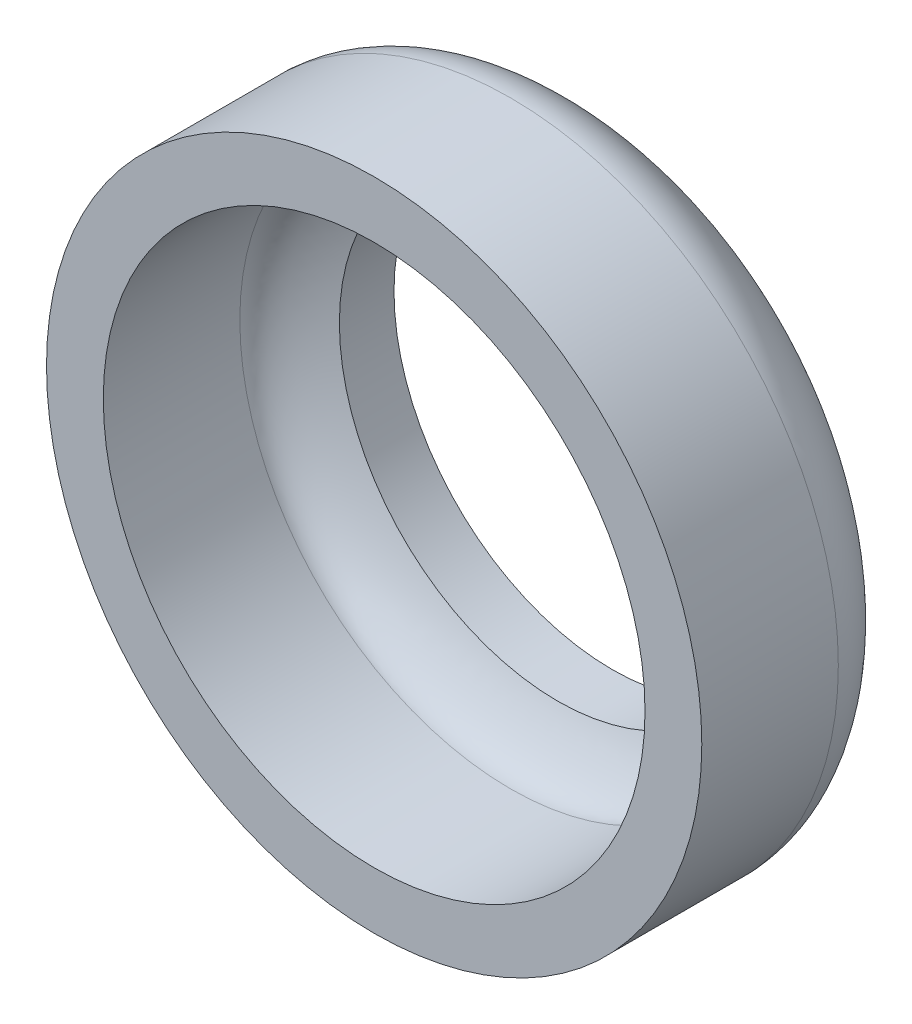
SolidWorks part; units mm, degrees
ref_plane "Front Plane" through (0, 0, 0) normal (0, 0, 1) x (1, 0, 0)
ref_plane "Top Plane" through (0, 0, 0) normal (0, 1, 0) x (1, 0, 0)
ref_plane "Right Plane" through (0, 0, 0) normal (1, 0, 0) x (0, 0, -1)
sketch "Sketch1" plane through (0, 0, 0) normal (1, 0, 0) x (0, 0, -1)
  line L0 (0, -9.525) -> (0, 9.525) construction
  line L1 (0, 0) -> (7.9375, 0) construction
  point P4 (0, 7.874)
  dimension "Tube OD" = 19.05
  dimension "Length" = 7.9375
  dimension "Wall Thickness" = 1.651
sketch "Sketch2" plane through (0, 0, 0) normal (1, 0, 0) x (0, 0, -1)
  line L0 (0, 9.525) -> (3.9688, 9.525)
  line L2 (0, 7.874) -> (3.9688, 7.874)
  line L4 (0, 0) -> (7.9375, 0) construction
  line L5 (6.2865, 0) -> (7.9375, 0)
  line L6 (0, 9.525) -> (0, 7.874)
  ellipse E0 centre (3.9688, 0) end of major axis (3.9688, 9.525) minor radius 3.9688 (7.9375, 0) -> (3.9688, 9.525) ccw
  ellipse E1 centre (3.9688, 0) end of major axis (3.9688, 7.874) minor radius 2.3178 (6.2865, 0) -> (3.9688, 7.874) ccw
revolve "Revolve1" add sketch "Sketch2" angle 360 about L1
sketch "Sketch3" plane through (0, 0, 0) normal (0, 0, 1) x (1, 0, 0)
  circle A0 centre (0, 0) radius 6.35
  dimension "D1" = 12.7
extrude "Cut-Extrude1" cut sketch "Sketch3" against normal through all both
